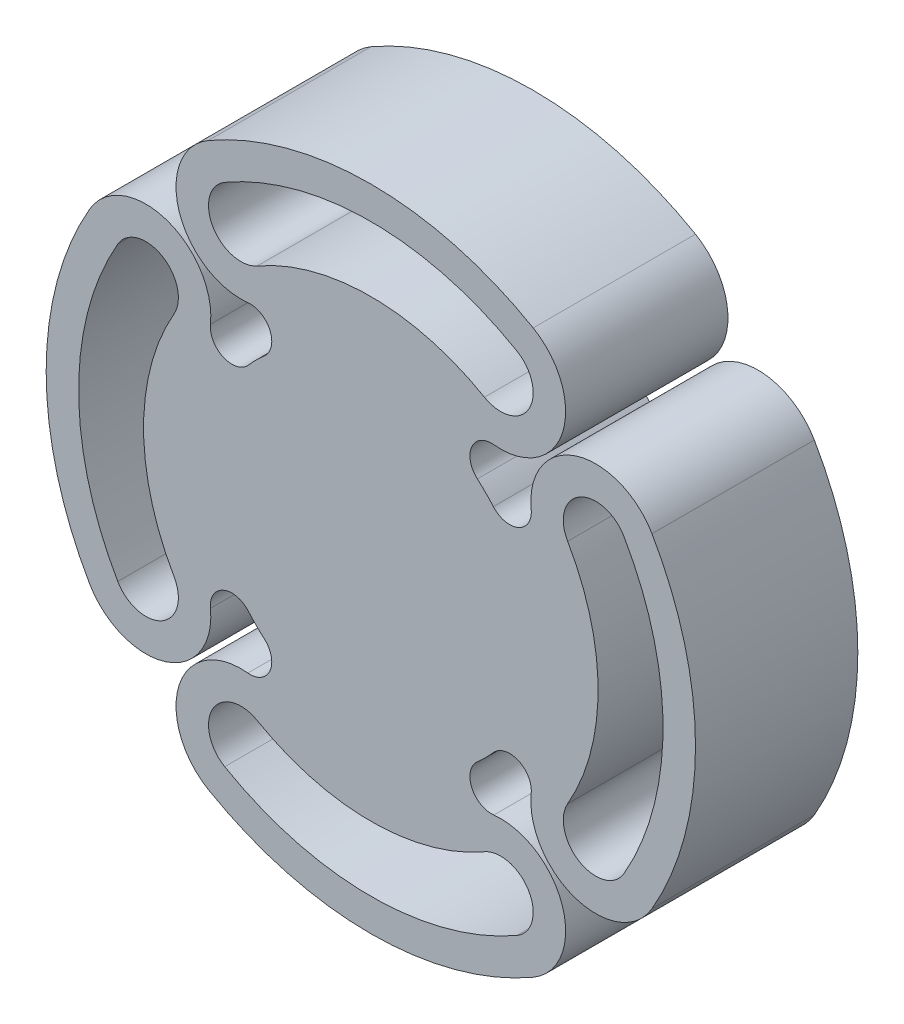
SolidWorks part; units mm, degrees
ref_plane "Front Plane" through (0, 0, 0) normal (0, 0, 1) x (1, 0, 0)
ref_plane "Top Plane" through (0, 0, 0) normal (0, 1, 0) x (1, 0, 0)
ref_plane "Right Plane" through (0, 0, 0) normal (1, 0, 0) x (0, 0, -1)
sketch "Sketch1" plane through (0, 0, 0) normal (0, 0, 1) x (1, 0, 0)
  line L0 (0, 0) -> (0, 14816.9797) construction
  line L1 (0, 0) -> (14816.9797, 0) construction
  arc A0 (11.3202, 9.8415) -> (9.8415, 11.3202) centre (0, 0) ccw
  arc A1 (20.7846, -12) -> (20.7846, 12) centre (0, 0) ccw construction
  arc A2 (23.3827, -13.5) -> (23.3827, 13.5) centre (0, 0) ccw
  arc A3 (18.1865, -10.5) -> (18.1865, 10.5) centre (0, 0) ccw
  arc A4 (18.1865, -10.5) -> (23.3827, -13.5) centre (20.7846, -12) ccw
  arc A5 (23.3827, 13.5) -> (18.1865, 10.5) centre (20.7846, 12) ccw
  arc A6 (25.9808, -15) -> (25.9808, 15) centre (0, 0) ccw
  arc A7 (25.9808, 15) -> (14.8183, 11.3652) centre (20.7846, 12) ccw
  arc A9 (14.8183, -11.3652) -> (25.9808, -15) centre (20.7846, -12) ccw
  arc A10 (11.3202, 9.8415) -> (14.8183, 11.3652) centre (12.8295, 11.1536) ccw
  arc A11 (11.3202, -9.8415) -> (14.8183, -11.3652) centre (12.8295, -11.1536) cw
  arc A12 (-10.5, -18.1865) -> (10.5, -18.1865) centre (0, 0) ccw
  arc A13 (25.9808, 15) -> (15.5885, 9) centre (20.7846, 12) ccw construction
  arc A14 (15.5885, -9) -> (15.5885, 9) centre (0, 0) ccw construction
  arc A15 (15.5885, -9) -> (25.9808, -15) centre (20.7846, -12) ccw construction
  arc A16 (-10.5, -18.1865) -> (-13.5, -23.3827) centre (-12, -20.7846) ccw
  arc A17 (13.5, -23.3827) -> (10.5, -18.1865) centre (12, -20.7846) ccw
  arc A18 (-13.5, -23.3827) -> (13.5, -23.3827) centre (0, 0) ccw
  arc A19 (-15, -25.9808) -> (15, -25.9808) centre (0, 0) ccw
  arc A20 (15, -25.9808) -> (11.3652, -14.8183) centre (12, -20.7846) ccw
  arc A21 (9.8415, -11.3202) -> (11.3652, -14.8183) centre (11.1536, -12.8295) ccw
  arc A22 (-11.3652, -14.8183) -> (-15, -25.9808) centre (-12, -20.7846) ccw
  arc A23 (-9.8415, -11.3202) -> (-11.3652, -14.8183) centre (-11.1536, -12.8295) cw
  arc A24 (-12, -20.7846) -> (12, -20.7846) centre (0, 0) ccw construction
  arc A25 (-18.1865, 10.5) -> (-18.1865, -10.5) centre (0, 0) ccw
  arc A26 (-18.1865, 10.5) -> (-23.3827, 13.5) centre (-20.7846, 12) ccw
  arc A27 (-23.3827, -13.5) -> (-18.1865, -10.5) centre (-20.7846, -12) ccw
  arc A28 (-23.3827, 13.5) -> (-23.3827, -13.5) centre (0, 0) ccw
  arc A29 (-25.9808, 15) -> (-25.9808, -15) centre (0, 0) ccw
  arc A30 (-25.9808, -15) -> (-14.8183, -11.3652) centre (-20.7846, -12) ccw
  arc A31 (-11.3202, -9.8415) -> (-14.8183, -11.3652) centre (-12.8295, -11.1536) ccw
  arc A32 (-14.8183, 11.3652) -> (-25.9808, 15) centre (-20.7846, 12) ccw
  arc A33 (-11.3202, 9.8415) -> (-14.8183, 11.3652) centre (-12.8295, 11.1536) cw
  arc A34 (-20.7846, 12) -> (-20.7846, -12) centre (0, 0) ccw construction
  arc A35 (10.5, 18.1865) -> (-10.5, 18.1865) centre (0, 0) ccw
  arc A36 (10.5, 18.1865) -> (13.5, 23.3827) centre (12, 20.7846) ccw
  arc A37 (-13.5, 23.3827) -> (-10.5, 18.1865) centre (-12, 20.7846) ccw
  arc A38 (13.5, 23.3827) -> (-13.5, 23.3827) centre (0, 0) ccw
  arc A39 (15, 25.9808) -> (-15, 25.9808) centre (0, 0) ccw
  arc A40 (-15, 25.9808) -> (-11.3652, 14.8183) centre (-12, 20.7846) ccw
  arc A41 (-9.8415, 11.3202) -> (-11.3652, 14.8183) centre (-11.1536, 12.8295) ccw
  arc A42 (11.3652, 14.8183) -> (15, 25.9808) centre (12, 20.7846) ccw
  arc A43 (9.8415, 11.3202) -> (11.3652, 14.8183) centre (11.1536, 12.8295) cw
  arc A44 (12, 20.7846) -> (-12, 20.7846) centre (0, 0) ccw construction
  arc A45 (-9.8415, 11.3202) -> (-11.3202, 9.8415) centre (0, 0) ccw
  arc A46 (-11.3202, -9.8415) -> (-9.8415, -11.3202) centre (0, 0) ccw
  arc A47 (9.8415, -11.3202) -> (11.3202, -9.8415) centre (0, 0) ccw
  point P9 (24, 0)
  point P32 (0, -24)
  point P49 (-24, 0)
  point P66 (0, 24)
  point P81 (0, 0)
  dimension "D1" = 30
  dimension "D2" = 24
  dimension "D4" = 27
  dimension "D5" = 3
  dimension "D6" = 2
  dimension "D7" = 2
  dimension "D3" = 60
extrude "Boss-Extrude1" add sketch "Sketch1" along normal mid plane 15
